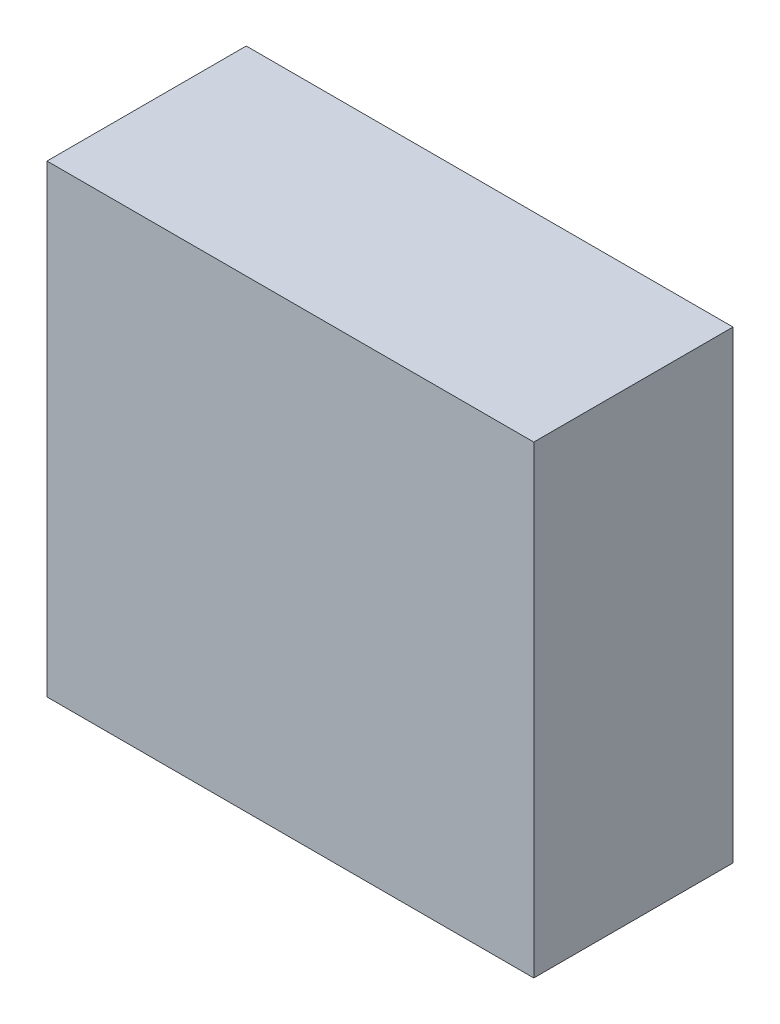
SolidWorks part; units mm, degrees
ref_plane "Front Plane" through (0, 0, 0) normal (0, 0, 1) x (1, 0, 0)
ref_plane "Top Plane" through (0, 0, 0) normal (0, 1, 0) x (1, 0, 0)
ref_plane "Right Plane" through (0, 0, 0) normal (1, 0, 0) x (0, 0, -1)
sketch "Sketch1" plane through (0, 0, 0) normal (0, 0, 1) x (1, 0, 0)
  line L1 (-21.5, -20.5) -> (21.5, -20.5)
  line L2 (-21.5, -20.5) -> (-21.5, 20.5)
  line L3 (-21.5, 20.5) -> (21.5, 20.5)
  line L4 (21.5, -20.5) -> (21.5, 20.5)
  line L5 (-21.5, -20.5) -> (21.5, 20.5) construction
  line L6 (-21.5, 20.5) -> (21.5, -20.5) construction
extrude "Envelope" add sketch "Sketch1" along normal blind 17.6
